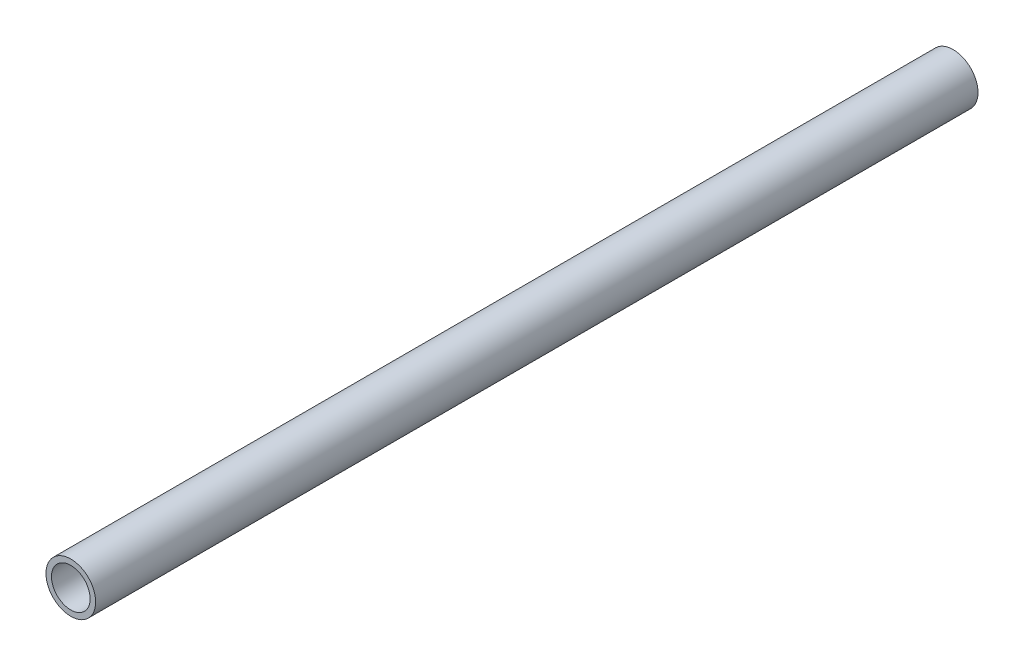
SolidWorks part; units mm, degrees
ref_plane "Front Plane" through (0, 0, 0) normal (0, 0, 1) x (1, 0, 0)
ref_plane "Top Plane" through (0, 0, 0) normal (0, 1, 0) x (1, 0, 0)
ref_plane "Right Plane" through (0, 0, 0) normal (1, 0, 0) x (0, 0, -1)
sketch "Sketch1" plane through (0, 0, 0) normal (0, 0, 1) x (1, 0, 0)
  circle A0 centre (0, 0) radius 9
  circle A1 centre (0, 0) radius 7
  dimension "D1" = 14
  dimension "D2" = 18
extrude "Boss-Extrude1" add sketch "Sketch1" along normal blind 319.6
